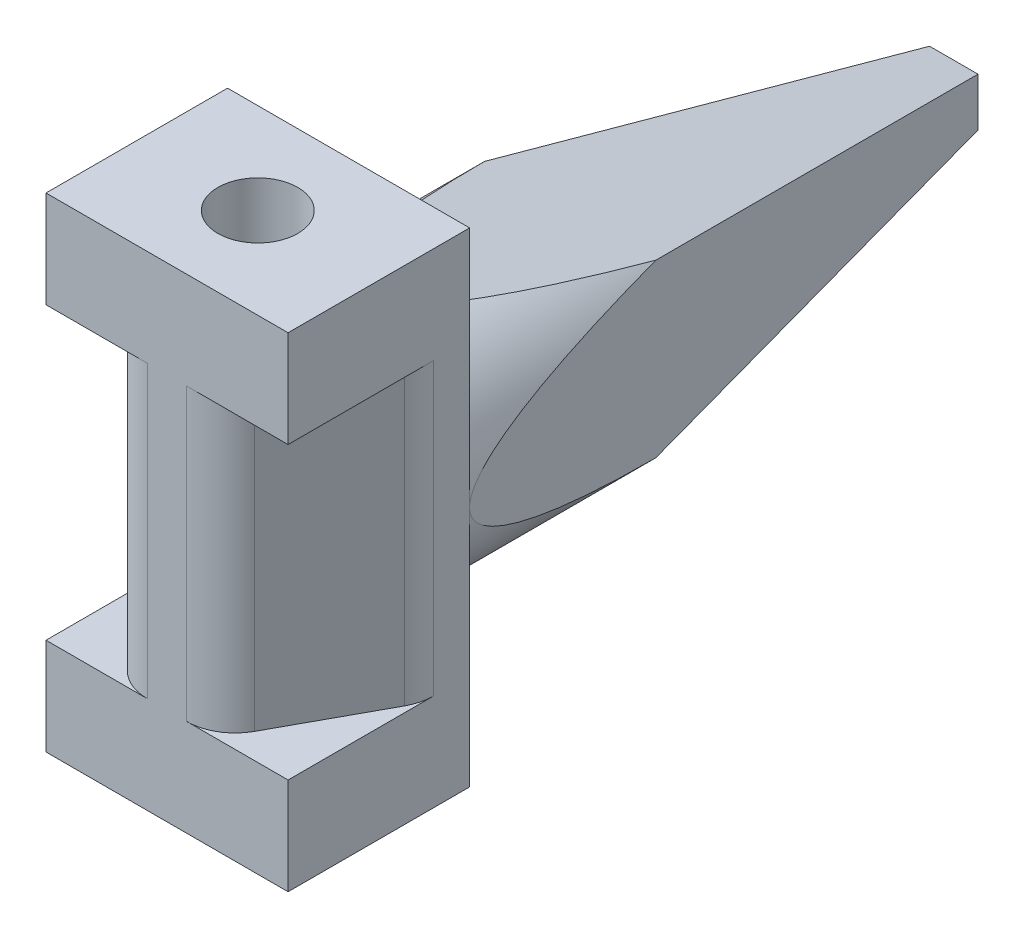
SolidWorks part; units mm, degrees
material "ABS"
ref_plane "Front Plane" through (0, 0, 0) normal (0, 0, 1) x (1, 0, 0)
ref_plane "Top Plane" through (0, 0, 0) normal (0, 1, 0) x (1, 0, 0)
ref_plane "Right Plane" through (0, 0, 0) normal (1, 0, 0) x (0, 0, -1)
sketch "Sketch1" plane through (0, 0, 0) normal (0, 1, 0) x (1, 0, 0)
  line L0 (-10, 7.5) -> (-10, 6.01)
  line L1 (0, 0) -> (-10, 0)
  line L2 (0, 0) -> (0, 7.5)
  line L3 (0, 7.5) -> (-10, 7.5)
  line L4 (-10, 0) -> (-10, 7.5)
  line L5 (-9.7558, 5.0523) -> (-7.5685, 1.0423)
  line L6 (-5.8127, 0) -> (-5, 0)
  line L7 (-5, 0) -> (-5, 7.5)
  line L8 (-0.2442, 5.0523) -> (-2.4315, 1.0423)
  arc A0 (-10, 6.01) -> (-9.7558, 5.0523) centre (-8, 6.01) ccw
  arc A1 (-7.5685, 1.0423) -> (-5.8127, 0) centre (-5.8127, 2) ccw
  arc A2 (-2.4315, 1.0423) -> (-4.1873, 0) centre (-4.1873, 2) cw
  arc A3 (0, 6.01) -> (-0.2442, 5.0523) centre (-2, 6.01) cw
  circle A4 centre (-5, 3.75) radius 1.65
  point P11 (-10, 5.5)
  point P14 (-7, 0)
  dimension "D5" = 2
  dimension "D6" = 3.3
  dimension "D1" = 10
  dimension "D2" = 7.5
  dimension "D3" = 2
  dimension "D4" = 2
  dimension "D7" = 3.75
extrude "Boss-Extrude1" add sketch "Sketch1" along normal blind 12 contours A4 L7 L3 L0 A0 L5 A1 L1 | A4 L7 L1 A2 L8 A3 L2 L3
sketch "Sketch2" plane through (0, 0, 0) normal (0, -1, 0) x (1, 0, 0)
  line L1 (-10, 0) -> (0, 0)
  line L2 (-10, 0) -> (-10, -7.5)
  line L3 (-10, -7.5) -> (0, -7.5)
  line L4 (0, 0) -> (0, -7.5)
  line L5 (-10, 0) -> (0, -7.5) construction
  line L6 (-10, -7.5) -> (0, 0) construction
  circle A0 centre (-5, -3.75) radius 1.65
  point P0 (-5, -3.75)
  dimension "D1" = 3.3
extrude "Boss-Extrude2" add sketch "Sketch2" along normal blind 4
sketch "Sketch3" plane through (0, 12, 0) normal (0, 1, 0) x (1, 0, 0)
  line L1 (0, 0) -> (-10, 0)
  line L2 (0, 0) -> (0, 7.5)
  line L3 (0, 7.5) -> (-10, 7.5)
  line L4 (-10, 0) -> (-10, 7.5)
  line L5 (0, 0) -> (-10, 7.5) construction
  line L6 (0, 7.5) -> (-10, 0) construction
  circle A0 centre (-5, 3.75) radius 1.65
  point P0 (-5, 3.75)
  dimension "D1" = 3.3
extrude "Boss-Extrude3" add sketch "Sketch3" along normal blind 4
sketch "Sketch4" plane through (0, 0, -7.5) normal (0, 0, -1) x (-1, 0, 0)
  line L0 (10, 16) -> (10, -4) construction
  line L1 (10, -4) -> (0, -4) construction
  circle A0 centre (5, 6) radius 5
  dimension "D1" = 10
  dimension "D2" = 5
  dimension "D3" = 10
extrude "Boss-Extrude4" add sketch "Sketch4" along normal blind 25
sketch "Sketch5" plane through (0, 0, 0) normal (1, 0, 0) x (0, 0, -1)
  line L0 (7.5, 11) -> (32.5, 7)
  line L1 (7.5, 16) -> (7.5, 6) construction
  line L2 (32.5, 1) -> (32.5, 11) construction
  line L3 (32.5, 5) -> (7.5, 1)
  line L5 (7.5, 1) -> (32.5, 1)
  line L6 (32.5, 1) -> (32.5, 11)
  line L7 (32.5, 11) -> (7.5, 11)
  point P7 (32.5, 6)
  dimension "D1" = 1
  dimension "D2" = 1
extrude "Cut-Extrude1" cut sketch "Sketch5" against normal through all contours L6 L7 L0 | L5 L6 L3
sketch "Sketch6" plane through (0, -4, 0) normal (0, -1, 0) x (-1, 0, 0)
  line L5 (5, 32.5) -> (5, 7.5)
  line L6 (9.899, 32.5) -> (0.101, 32.5) construction
  line L7 (10, 7.5) -> (0, 7.5) construction
  line L8 (0, 7.5) -> (4, 32.5)
  line L9 (0, 32.5) -> (10, 32.5)
  line L10 (0, 32.5) -> (0, 7.5)
  line L11 (0, 7.5) -> (10, 7.5)
  line L12 (10, 32.5) -> (10, 7.5)
  line L13 (0, 32.5) -> (10, 7.5) construction
  line L14 (0, 7.5) -> (10, 32.5) construction
  line L15 (6, 32.5) -> (10, 7.5)
  point P7 (5, 20)
  dimension "D1" = 1
  dimension "D2" = 1
extrude "Cut-Extrude2" cut sketch "Sketch6" against normal through all contours L9 L10 L8 | L9 L15 L12
